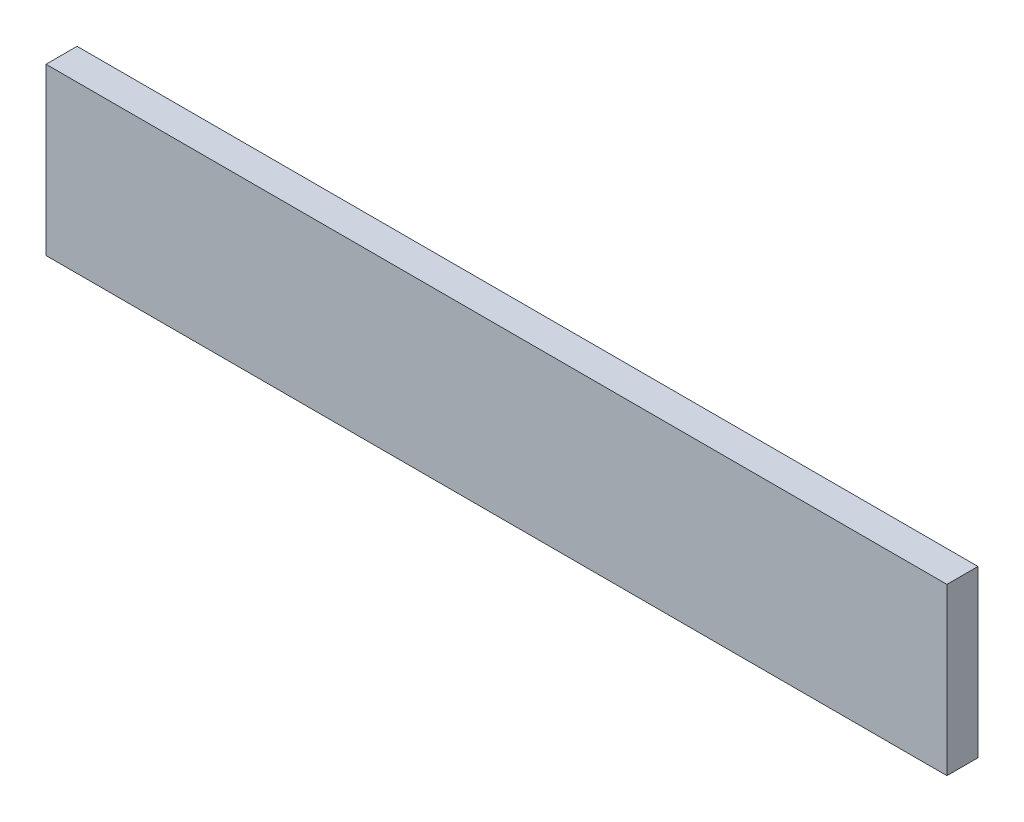
SolidWorks part; units mm, degrees
material "Pine"
ref_plane "Front Plane" through (0, 0, 0) normal (0, 0, 1) x (1, 0, 0)
ref_plane "Top Plane" through (0, 0, 0) normal (0, 1, 0) x (1, 0, 0)
ref_plane "Right Plane" through (0, 0, 0) normal (1, 0, 0) x (0, 0, -1)
sketch "Sketch1" plane through (0, 0, 0) normal (0, 0, 1) x (1, 0, 0)
  line L1 (-276.225, -50.8) -> (276.225, -50.8)
  line L2 (-276.225, -50.8) -> (-276.225, 50.8)
  line L3 (-276.225, 50.8) -> (276.225, 50.8)
  line L4 (276.225, -50.8) -> (276.225, 50.8)
  line L5 (-276.225, -50.8) -> (276.225, 50.8) construction
  line L6 (-276.225, 50.8) -> (276.225, -50.8) construction
  point P0 (0, 0)
  dimension "D1" = 552.45
  dimension "D2" = 101.6
extrude "Boss-Extrude1" add sketch "Sketch1" against normal blind 19.05
